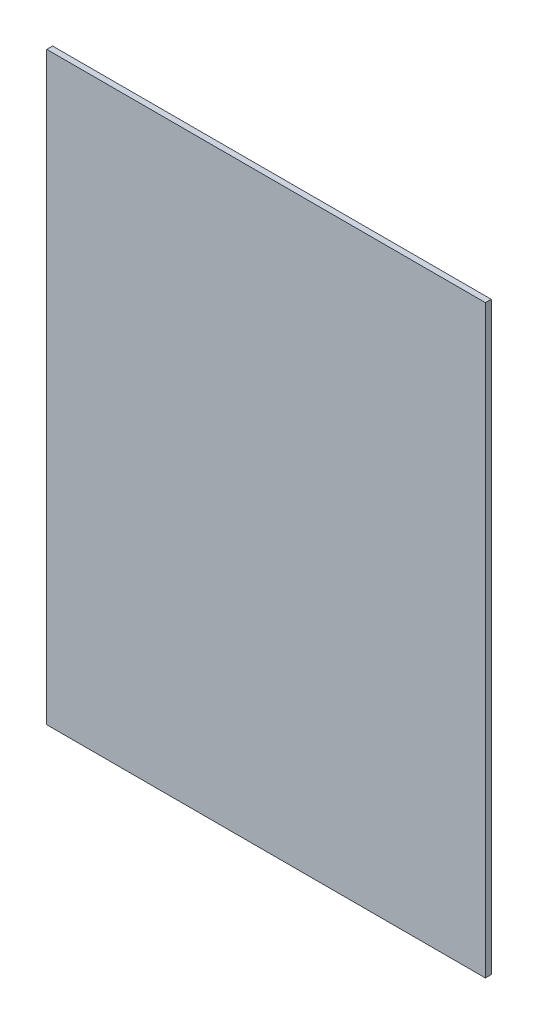
SolidWorks part; units mm, degrees
ref_plane "Ebene vorne" through (0, 0, 0) normal (1, 0, 0) x (0, 1, 0)
ref_plane "Ebene oben" through (0, 0, 0) normal (0, 0, 1) x (0, 1, 0)
ref_plane "Ebene rechts" through (0, 0, 0) normal (0, 1, 0) x (-1, 0, 0)
sketch "Skizze1" plane through (0, 0, 0) normal (0, 0, 1) x (0, 1, 0)
  line L1 (-100, -75) -> (100, -75)
  line L2 (-100, -75) -> (-100, 75)
  line L3 (-100, 75) -> (100, 75)
  line L4 (100, -75) -> (100, 75)
  line L5 (-100, -75) -> (100, 75) construction
  line L6 (-100, 75) -> (100, -75) construction
  point P0 (0, 0)
  dimension "D1" = 150
  dimension "D2" = 200
extrude "Aufsatz-Linear austragen1" add sketch "Skizze1" along normal blind 2
